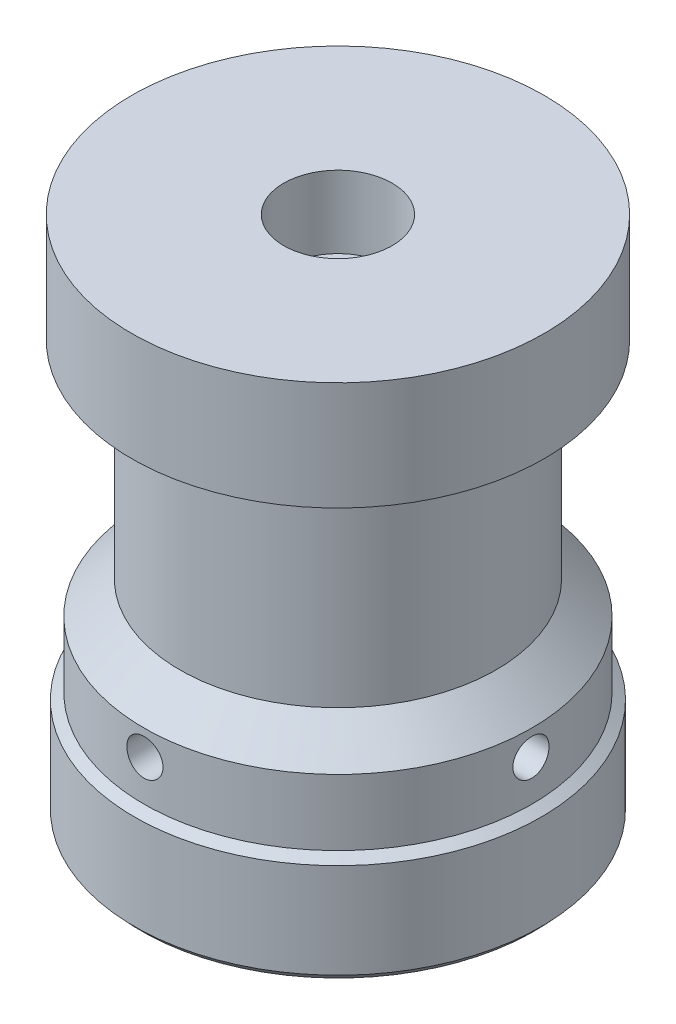
SolidWorks part; units mm, degrees
ref_plane "Front Plane" through (0, 0, 0) normal (0, 0, 1) x (1, 0, 0)
ref_plane "Top Plane" through (0, 0, 0) normal (0, 1, 0) x (1, 0, 0)
ref_plane "Right Plane" through (0, 0, 0) normal (1, 0, 0) x (0, 0, -1)
sketch "Sketch1" plane through (0, 0, 0) normal (0, 0, 1) x (1, 0, 0)
  line L0 (0, 0) -> (0, 41.5041) construction
  line L1 (11, 0) -> (11, 41.4)
  line L2 (11, 41.4) -> (3.25, 41.4)
  line L3 (3.25, 41.4) -> (3.25, 49.8)
  line L4 (3.25, 49.8) -> (6, 49.8)
  line L5 (6, 49.8) -> (6, 57.8)
  line L6 (6, 57.8) -> (22.825, 57.8)
  line L7 (22.825, 57.8) -> (22.825, 45.8)
  line L8 (22.825, 45.8) -> (17.5, 45.8)
  line L9 (17.5, 45.8) -> (17.5, 22.9)
  line L10 (17.5, 22.9) -> (21.45, 19.3)
  line L11 (21.45, 19.3) -> (21.45, 12)
  line L12 (21.45, 12) -> (22.5, 11.3)
  line L13 (22.5, 11.3) -> (22.5, 0.8)
  line L14 (22.5, 0.8) -> (21.75, 0)
  line L15 (21.75, 0) -> (11, 0)
  dimension "D1" = 22
  dimension "D2" = 57.8
  dimension "D3" = 12
  dimension "D4" = 12
  dimension "D5" = 6.5
  dimension "D6" = 8
  dimension "D7" = 45.65
  dimension "D8" = 19.3
  dimension "D9" = 7.3
  dimension "D10" = 45
  dimension "D11" = 22.9
  dimension "D12" = 42.9
  dimension "D13" = 11.3
  dimension "D14" = 0.8
  dimension "D15" = 43.5
  dimension "D16" = 35
  dimension "D17" = 41.4
revolve "Revolve1" add sketch "Sketch1" angle 360 about L0
sketch "Sketch2" plane through (0, 0, 0) normal (0, -1, 0) x (1, 0, 0)
  line L0 (0, 10.5) -> (0, 0) construction
  line L1 (-3, 14) -> (3, 14)
  line L2 (-3, 14) -> (-3, 7)
  line L3 (-3, 7) -> (3, 7)
  line L4 (3, 14) -> (3, 7)
  line L5 (-3, 14) -> (3, 7) construction
  line L6 (-3, 7) -> (3, 14) construction
  line L7 (0, 0) -> (0, -11) construction
  circle A0 centre (0, 0) radius 11 construction
  circle A1 centre (0, 0) radius 11 construction
  point P0 (0, 10.5)
  point P14 (0, -11)
  dimension "D1" = 6
  dimension "D2" = 7
  dimension "D3" = 18
extrude "Cut-Extrude1" cut sketch "Sketch2" against normal up to surface (41.4 mm away) up to face at (0, 41.4, -11)
ref_plane "Plane1" through (0, 0, 22) normal (0, 0, 1) x (1, 0, 0)
sketch "Sketch3" plane through (0, 0, 22) normal (0, 0, 1) x (1, 0, 0)
  line L0 (0, 0) -> (0, 16.5) construction
  circle A1 centre (0, 16.5) radius 2
  dimension "D2" = 4
  dimension "D1" = 16.5
ref_plane "Plane2" through (22, 0, 0) normal (1, 0, 0) x (0, 0, -1)
sketch "Sketch4" plane through (22, 0, 0) normal (1, 0, 0) x (0, 0, -1)
  line L0 (-22, 16.5) -> (0, 16.5) construction
  line L2 (0, 0) -> (0, 16.5) construction
  line L3 (-22, 0) -> (-22, 16.5) construction
  circle A0 centre (0, 16.5) radius 2
  point P0 (0, 16.5)
  dimension "D1" = 4
extrude "Cut-Extrude2" cut sketch "Sketch3" against normal blind 29
extrude "Cut-Extrude3" cut sketch "Sketch4" against normal blind 29
